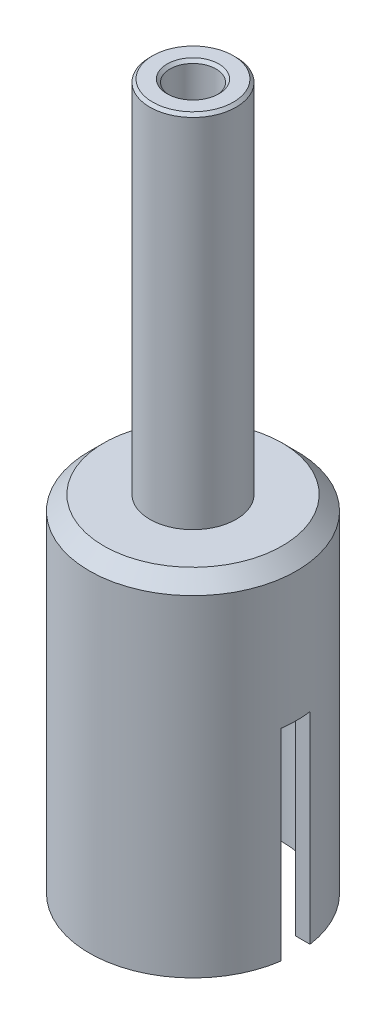
SolidWorks part; units mm, degrees
material "Lega 1345"
ref_plane "Piano frontale" through (0, 0, 0) normal (0, 0, 1) x (1, 0, 0)
ref_plane "Piano superiore" through (0, 0, 0) normal (0, 1, 0) x (1, 0, 0)
ref_plane "Piano destro" through (0, 0, 0) normal (1, 0, 0) x (0, 0, -1)
sketch "Schizzo1" plane through (0, 0, 0) normal (0, 1, 0) x (1, 0, 0)
  circle A0 centre (0, 0) radius 36
  dimension "D1" = 72
extrude "Estrusione1" add sketch "Schizzo1" along normal blind 120
sketch "Schizzo2" plane through (0, 0, 0) normal (0, -1, 0) x (1, 0, 0)
  circle A0 centre (0, 0) radius 31
  dimension "D1" = 62
extrude "Estrusione2" cut sketch "Schizzo2" against normal blind 110
chamfer "Smusso1" distance 5 angle 45 1 edges at (0, 120, 36)
sketch "Schizzo3" plane through (0, 120, 0) normal (0, 1, 0) x (1, 0, 0)
  circle A0 centre (0, 0) radius 15
  dimension "D1" = 30
extrude "Estrusione3" add sketch "Schizzo3" along normal blind 125
sketch "Schizzo4" plane through (0, 245, 0) normal (0, 1, 0) x (1, 0, 0)
  circle A0 centre (0, 0) radius 8
  dimension "D1" = 16
extrude "Estrusione4" cut sketch "Schizzo4" against normal through all
chamfer "Smusso2" distance 1 angle 45 2 edges at (0, 245, 8) (0, 245, 15)
sketch "Schizzo5" plane through (0, 0, 0) normal (0, -1, 0) x (1, 0, 0)
  line L1 (-44.1687, -5) -> (44.1687, -5)
  line L2 (-44.1687, -5) -> (-44.1687, 5)
  line L3 (-44.1687, 5) -> (44.1687, 5)
  line L4 (44.1687, -5) -> (44.1687, 5)
  line L5 (-44.1687, -5) -> (44.1687, 5) construction
  line L6 (-44.1687, 5) -> (44.1687, -5) construction
  point P0 (0, 0)
  dimension "D1" = 10
extrude "Estrusione5" cut sketch "Schizzo5" against normal blind 70
